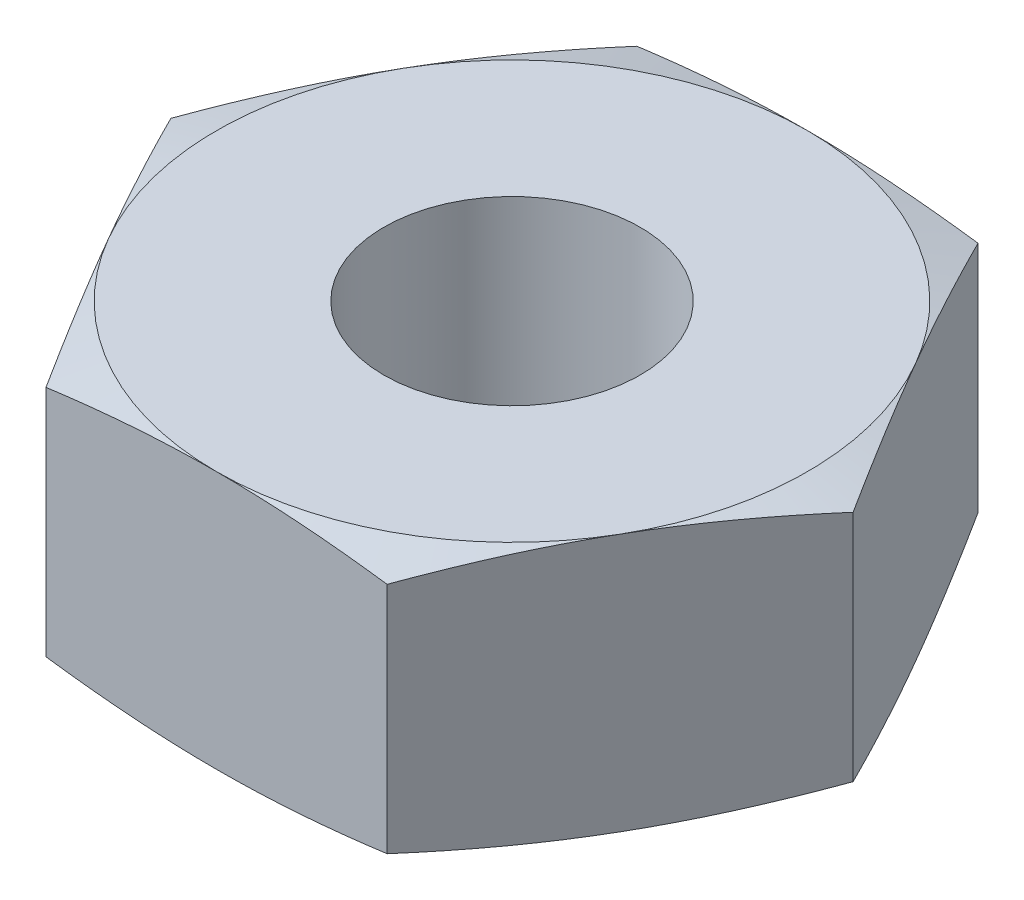
SolidWorks part; units mm, degrees
material "Plain Carbon Steel"
ref_plane "Front Plane" through (0, 0, 0) normal (0, 0, 1) x (1, 0, 0)
ref_plane "Top Plane" through (0, 0, 0) normal (0, 1, 0) x (1, 0, 0)
ref_plane "Right Plane" through (0, 0, 0) normal (1, 0, 0) x (0, 0, -1)
sketch "Sketch1" plane through (0, 0, 0) normal (0, 1, 0) x (1, 0, 0)
  line L1 (3.1754, 0) -> (1.5877, 2.75)
  line L2 (1.5877, 2.75) -> (-1.5877, 2.75)
  line L3 (-1.5877, 2.75) -> (-3.1754, 0)
  line L4 (-3.1754, 0) -> (-1.5877, -2.75)
  line L5 (-1.5877, -2.75) -> (1.5877, -2.75)
  line L6 (1.5877, -2.75) -> (3.1754, 0)
  circle A0 centre (0, 0) radius 2.75 construction
  dimension "D1" = 5.5
extrude "Extrude1" add sketch "Sketch1" along normal mid plane 2.4
sketch "Sketch2" plane through (0, 0, 0) normal (1, 0, 0) x (0, 0, -1)
  line L0 (-2.75, 1.2) -> (-77.7802, -18.9043)
  line L1 (-77.7802, -18.9043) -> (-77.7802, 1.2)
  line L2 (-77.7802, 1.2) -> (-2.75, 1.2)
  line L3 (0, 0) -> (0, 7.9376) construction
  dimension "D1" = 15
revolve "Cut-Revolve1" cut sketch "Sketch2" angle 360 about L3
mirror "Mirror1" about plane through (0, 0, 0) normal (0, 1, 0) of "Cut-Revolve1"
sketch "Sketch3" plane through (0, 1.2, 0) normal (0, 1, 0) x (1, 0, 0)
  circle A0 centre (0, 0) radius 1.193
  dimension "D1" = 2.386
extrude "Extrude2" cut sketch "Sketch3" against normal through all
cosmetic thread "Cosmetic Thread1" parameters "D2"=3
